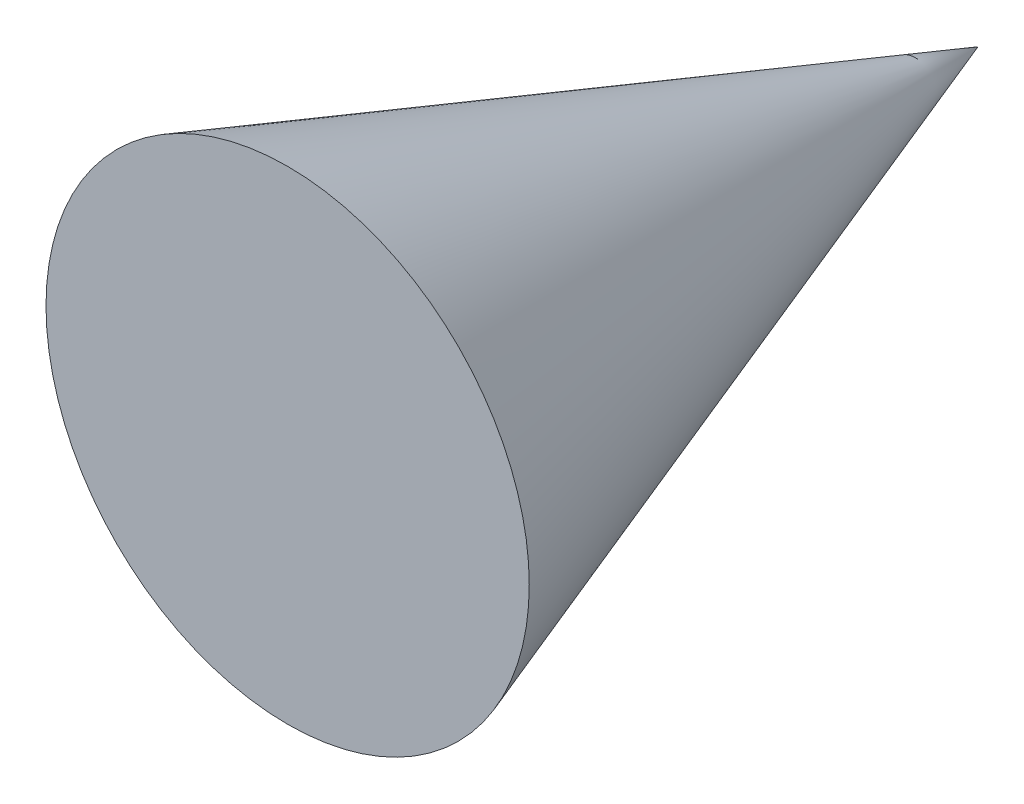
SolidWorks part; units mm, degrees
ref_plane "Front Plane" through (0, 0, 0) normal (0, 0, 1) x (1, 0, 0)
ref_plane "Top Plane" through (0, 0, 0) normal (0, 1, 0) x (1, 0, 0)
ref_plane "Right Plane" through (0, 0, 0) normal (1, 0, 0) x (0, 0, -1)
sketch "Sketch1" plane through (0, 0, 0) normal (0, 1, 0) x (1, 0, 0)
  line L4 (0, 0) -> (0, -20)
  line L5 (0, -20) -> (7, -20)
  line L6 (7, -20) -> (0, 0)
  dimension "D1" = 20
  dimension "D2" = 7
revolve "Revolve1" add sketch "Sketch1" angle 360 about L4
